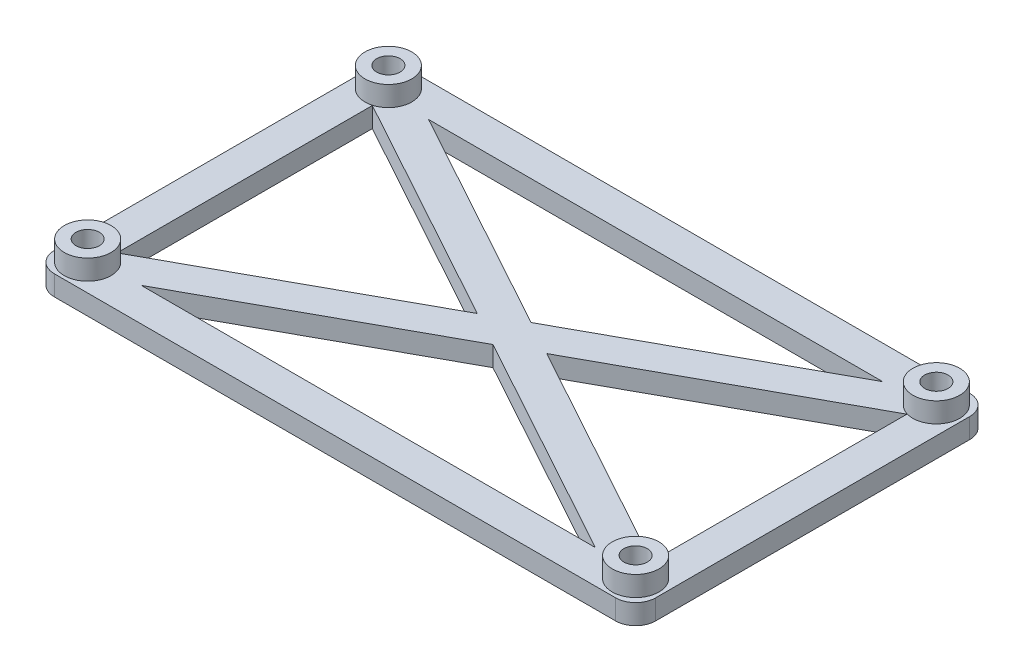
SolidWorks part; units mm, degrees
material "Acrílico (Impacto medio-alto)"
ref_plane "Alzado" through (0, 0, 0) normal (0, 0, 1) x (1, 0, 0)
ref_plane "Planta" through (0, 0, 0) normal (0, 1, 0) x (1, 0, 0)
ref_plane "Vista lateral" through (0, 0, 0) normal (1, 0, 0) x (0, 0, -1)
sketch "Croquis1" plane through (0, 0, 0) normal (0, 1, 0) x (1, 0, 0)
  line L1 (45, -26.5) -> (-45, -26.5)
  line L2 (45, -26.5) -> (45, 26.5)
  line L3 (45, 26.5) -> (-45, 26.5)
  line L4 (-45, -26.5) -> (-45, 26.5)
  line L5 (45, -26.5) -> (-45, 26.5) construction
  line L6 (45, 26.5) -> (-45, -26.5) construction
  point P0 (0, 0)
  dimension "D1" = 90
  dimension "D2" = 53
extrude "Saliente-Extruir1" add sketch "Croquis1" along normal blind 3
sketch "Croquis2" plane through (0, 0, 0) normal (0, -1, 0) x (1, 0, 0)
  circle A0 centre (41, -22.5) radius 1.75
  circle A1 centre (41, 22.5) radius 1.75
  circle A2 centre (-41, 22.5) radius 1.75
  circle A3 centre (-41, -22.5) radius 1.75
  dimension "D1" = 3.5
extrude "Cortar-Extruir1" cut sketch "Croquis2" against normal through all
sketch "Croquis3" plane through (0, 3, 0) normal (0, 1, 0) x (1, 0, 0)
  circle A0 centre (41, 22.5) radius 3.5
  circle A1 centre (-41, 22.5) radius 3.5
  circle A2 centre (-41, 22.5) radius 1.75 construction
  circle A3 centre (-41, 22.5) radius 1.75
  circle A4 centre (41, 22.5) radius 1.75 construction
  circle A5 centre (41, 22.5) radius 1.75
  dimension "D1" = 7
extrude "Saliente-Extruir2" add sketch "Croquis3" along normal blind 3
mirror "Simetría1" about plane through (0, 0, 0) normal (0, 0, 1) of "Saliente-Extruir2"
fillet "Redondeo1" radius 3 4 edges at (45, 1.5, -26.5) (-45, 1.5, -26.5) (-45, 1.5, 26.5) (45, 1.5, 26.5)
sketch "Croquis4" plane through (0, 0, 0) normal (0, -1, 0) x (1, 0, 0)
  line L0 (-41, 22.5) -> (41, -22.5) construction
  line L1 (41, 22.5) -> (-41, -22.5) construction
  line L2 (33.9813, 21.5) -> (0, 2.8517)
  line L3 (-40, 19.0995) -> (-5.1964, 0)
  line L4 (-33.9813, 21.5) -> (0, 2.8517)
  line L5 (40, 19.0995) -> (5.1964, 0)
  line L6 (-33.9813, 21.5) -> (33.9813, 21.5)
  line L7 (-40, -19.0995) -> (-40, 19.0995)
  line L8 (-42, 26.5) -> (42, 26.5) construction
  line L9 (33.9813, -21.5) -> (-33.9813, -21.5)
  line L10 (-45, -23.5) -> (-45, 23.5) construction
  line L11 (42, -26.5) -> (-42, -26.5) construction
  line L13 (0, -2.8517) -> (33.9813, -21.5)
  line L16 (-5.1964, 0) -> (-40, -19.0995)
  line L19 (-39.7973, 24.6917) -> (42.2027, -20.3083) construction
  line L20 (40, 23.5) -> (40, -23.5)
  line L21 (40, 19.0995) -> (40, -19.0995)
  line L22 (-42.2027, 20.3083) -> (39.7973, -24.6917) construction
  line L23 (39.7973, 24.6917) -> (-42.2027, -20.3083) construction
  line L24 (42.2027, 20.3083) -> (-39.7973, -24.6917) construction
  line L25 (5.1964, 0) -> (40, -19.0995)
  line L26 (0, -2.8517) -> (-33.9813, -21.5)
  dimension "D3" = 5
  dimension "D4" = 5
  dimension "D5" = 5
  dimension "D1" = 2.5
  dimension "D2" = 2.5
  dimension "D6" = 5
extrude "Cortar-Extruir2" cut sketch "Croquis4" against normal through all
